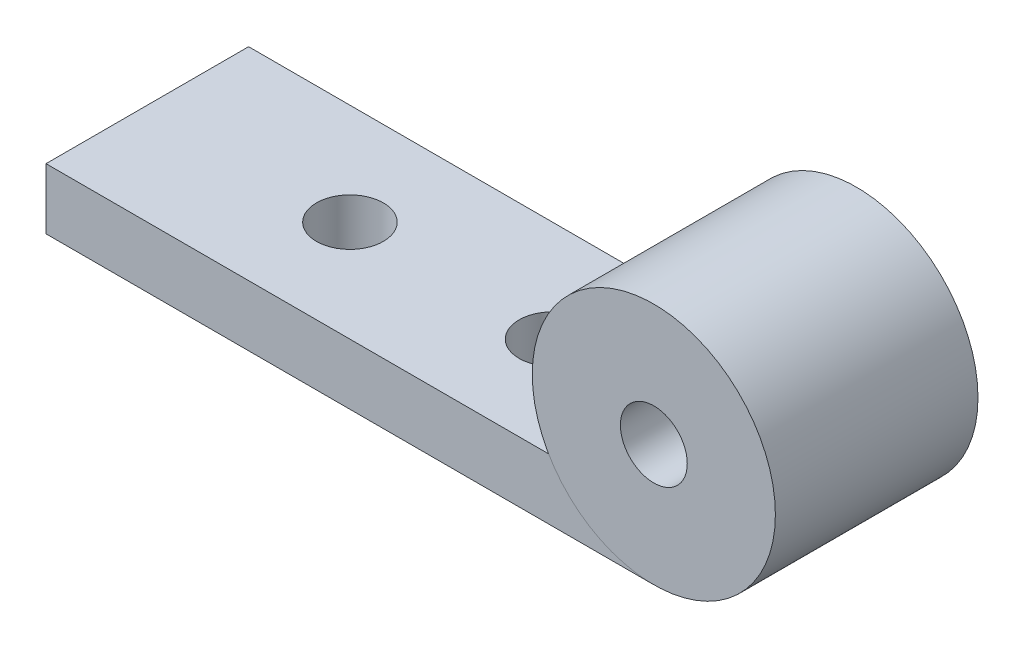
SolidWorks part; units mm, degrees
ref_plane "前视基准面" through (0, 0, 0) normal (0, 0, 1) x (1, 0, 0)
ref_plane "上视基准面" through (0, 0, 0) normal (0, 1, 0) x (1, 0, 0)
ref_plane "右视基准面" through (0, 0, 0) normal (1, 0, 0) x (0, 0, -1)
sketch "草图1" plane through (0, 0, 0) normal (0, 1, 0) x (1, 0, 0)
  line L1 (-15, -5) -> (15, -5)
  line L2 (-15, -5) -> (-15, 5)
  line L3 (-15, 5) -> (15, 5)
  line L4 (15, -5) -> (15, 5)
  line L5 (-15, -5) -> (15, 5) construction
  line L6 (-15, 5) -> (15, -5) construction
  circle A0 centre (-5, 0) radius 1.65
  circle A1 centre (5, 0) radius 1.65
  point P0 (0, 0)
  point P10 (0, 0)
  point P11 (-15, 0)
  point P12 (-5, 0)
  dimension "D3" = 3.3
  dimension "D4" = 3.3
  dimension "D1" = 10
  dimension "D2" = 30
  dimension "D5" = 10
  dimension "D6" = 10
extrude "凸台-拉伸1" add sketch "草图1" along normal blind 3
sketch "草图2" plane through (0, 0, 5) normal (0, 0, 1) x (1, 0, 0)
  line L1 (-15, 3) -> (-15, 0) construction
  line L2 (-15, 0) -> (15, 0) construction
  circle A0 centre (15, 6) radius 6
  circle A1 centre (15, 6) radius 1.65
  dimension "D1" = 3.3
  dimension "D2" = 12
  dimension "D3" = 30
extrude "凸台-拉伸2" add sketch "草图2" against normal blind 10 separate body
